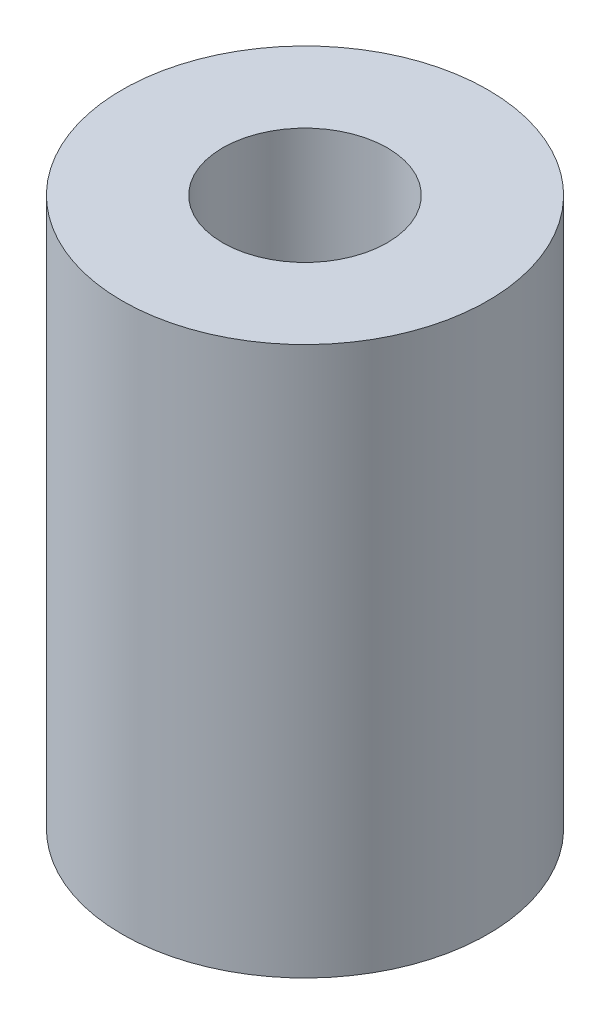
SolidWorks part; units mm, degrees
ref_plane "Front Plane" through (0, 0, 0) normal (0, 0, 1) x (1, 0, 0)
ref_plane "Top Plane" through (0, 0, 0) normal (0, 1, 0) x (1, 0, 0)
ref_plane "Right Plane" through (0, 0, 0) normal (1, 0, 0) x (0, 0, -1)
sketch "Sketch1" plane through (0, 0, 0) normal (0, 1, 0) x (1, 0, 0)
  circle A0 centre (0, 0) radius 12.7
  dimension "D1" = 25.4
extrude "Boss-Extrude1" add sketch "Sketch1" along normal blind 38.1
sketch "Sketch2" plane through (0, 38.1, 0) normal (0, 1, 0) x (1, 0, 0)
  circle A0 centre (0, 0) radius 5.715
  dimension "D1" = 11.43
extrude "Cut-Extrude1" cut sketch "Sketch2" against normal through all
sketch "Sketch3" plane through (0, 0, 0) normal (0, -1, 0) x (1, 0, 0)
  circle A0 centre (0, 0) radius 9.3345
  dimension "D1" = 18.669
extrude "Cut-Extrude2" cut sketch "Sketch3" against normal blind 12.7
